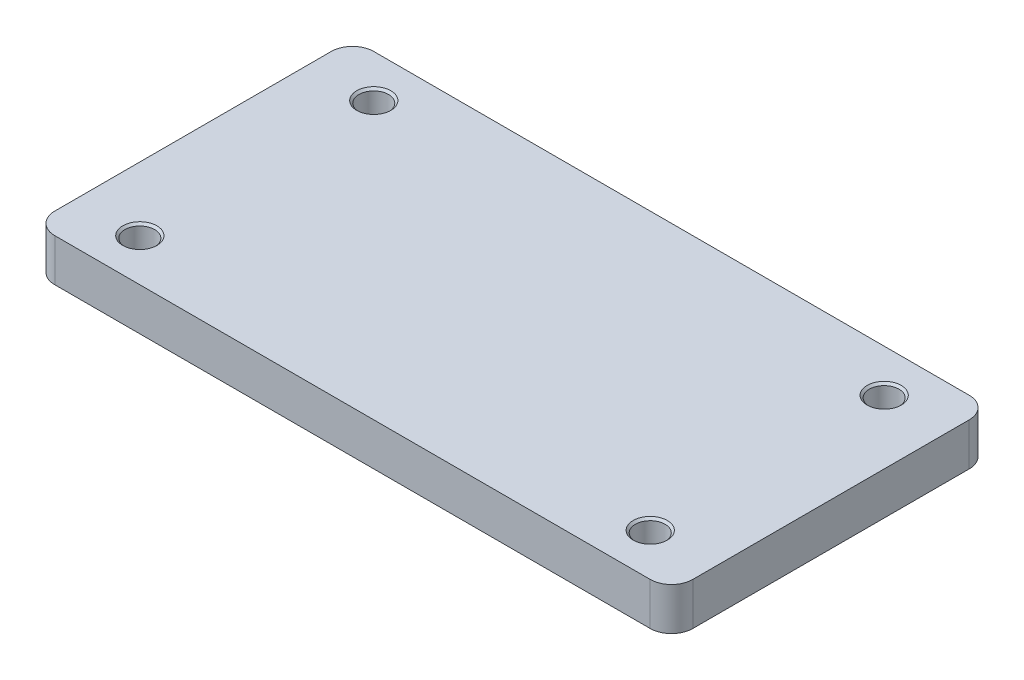
SolidWorks part; units mm, degrees
ref_plane "Front Plane" through (0, 0, 0) normal (0, 0, 1) x (1, 0, 0)
ref_plane "Top Plane" through (0, 0, 0) normal (0, 1, 0) x (1, 0, 0)
ref_plane "Right Plane" through (0, 0, 0) normal (1, 0, 0) x (0, 0, -1)
sketch "Sketch2" plane through (0, 0, 0) normal (0, 1, 0) x (1, 0, 0)
  line L1 (150, 75) -> (-150, 75)
  line L2 (150, 75) -> (150, -75)
  line L3 (150, -75) -> (-150, -75)
  line L4 (-150, 75) -> (-150, -75)
  point P4 (0, 75)
  point P6 (-150, 0)
  dimension "D1" = 300
  dimension "D2" = 150
extrude "Boss-Extrude1" add sketch "Sketch2" along normal mid plane 20
fillet "Fillet1" radius 10 4 edges at (-150, 0, -75) (150, 0, -75) (150, 0, 75) (-150, 0, 75)
sketch "Sketch3" plane through (0, 10, 0) normal (0, 1, 0) x (1, 0, 0)
  line L1 (120, 55) -> (-120, 55)
  line L2 (120, 55) -> (120, -55)
  line L3 (120, -55) -> (-120, -55)
  line L4 (-120, 55) -> (-120, -55)
  line L5 (120, 55) -> (-120, -55) construction
  line L6 (120, -55) -> (-120, 55) construction
  point P0 (0, 0)
  dimension "D1" = 240
  dimension "D2" = 110
hole_wizard "Ø17.0 (17) Diameter Hole1" positions "Sketch4" profile "Sketch5" hole size "Ø17.0" standard "ISO"
sketch "Sketch4" plane through (0, 10, 0) normal (0, 1, 0) x (1, 0, 0)
  point P0 (-120, 55)
  point P3 (120, 55)
  point P6 (120, -55)
  point P9 (-120, -55)
sketch "Sketch5" plane through (-120, 10, -55) normal (1, 0, 0) x (0, 0, 1)
  line L0 (0, 0) -> (0, 20)
  line L1 (0, 20) -> (8.5, 20)
  line L2 (8.5, 20) -> (8.5, 0.025)
  line L3 (8.5, 0.025) -> (8.525, 0)
  line L5 (8.525, 0) -> (0, 0)
  line L6 (-8.5, 0.025) -> (-8.525, 0) construction
  line L11 (0, -6.35) -> (0, 107.95) construction
  dimension "Thru Hole Dia." = 17
  dimension "Thru Hole Depth" = 20
  dimension "Near C'Sink Dia." = 17.05
  dimension "Near C'Sink Angle" = 90
hole_wizard "M16 Tapped Hole1" positions "3DSketch1" profile "Sketch6" tap size "M16" standard "ISO" end condition through all
sketch3d "3DSketch1"
  point P0 (-120, 10, -55)
  point P3 (120, 10, -55)
  point P6 (120, 10, 55)
  point P9 (-120, 10, 55)
sketch "Sketch6" plane through (-120, 10, -55) normal (1, 0, 0) x (0, 0, 1)
  line L0 (0, 0) -> (0, 20)
  line L1 (0, 20) -> (7, 20)
  line L2 (7, 20) -> (7, 1.025)
  line L3 (7, 1.025) -> (8.025, 0)
  line L5 (8.025, 0) -> (0, 0)
  line L6 (-7, 1.025) -> (-8.025, 0) construction
  line L11 (0, -6.35) -> (0, 107.95) construction
  dimension "Thru Tap Drill Dia." = 14
  dimension "Thru Tap Drill Depth" = 20
  dimension "Near C'Sink Dia." = 16.05
  dimension "Near C'Sink Angle" = 90
cosmetic thread "Hole Thread1" parameters "D2"=16
cosmetic thread "Hole Thread2" parameters "D2"=16
cosmetic thread "Hole Thread3" parameters "D2"=16
cosmetic thread "Hole Thread4" parameters "D2"=16
